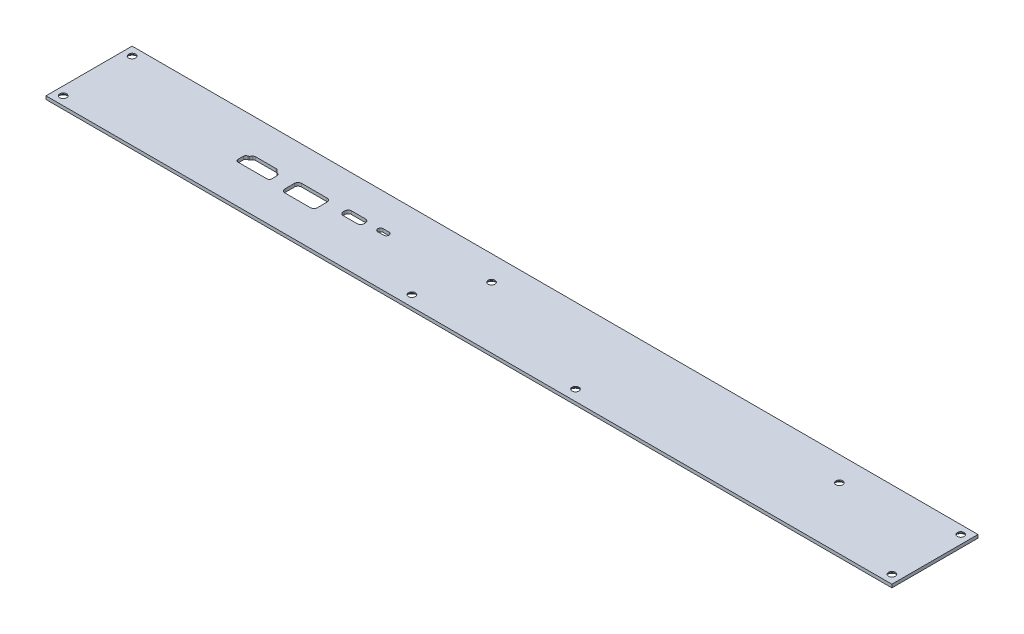
SolidWorks part; units mm, degrees
ref_plane "Ebene vorne" through (0, 0, 0) normal (0, 0, 1) x (1, 0, 0)
ref_plane "Ebene oben" through (0, 0, 0) normal (0, 1, 0) x (1, 0, 0)
ref_plane "Ebene rechts" through (0, 0, 0) normal (1, 0, 0) x (0, 0, -1)
sketch "Skizze1" plane through (0, 0, 0) normal (0, 1, 0) x (1, 0, 0)
  line L1 (-196.5, 20) -> (196.5, 20)
  line L2 (-196.5, 20) -> (-196.5, -20)
  line L3 (-196.5, -20) -> (196.5, -20)
  line L4 (196.5, 20) -> (196.5, -20)
  line L5 (-196.5, 20) -> (196.5, -20) construction
  line L6 (-196.5, -20) -> (196.5, 20) construction
  point P0 (0, 0)
extrude "Aufsatz-Linear austragen1" add sketch "Skizze1" along normal blind 1.5
sketch "Skizze2" plane through (0, 1.5, 0) normal (0, 1, 0) x (1, 0, 0)
  line L0 (196.5, -23) -> (-196.5, -23) construction
  line L5 (196.5, 20) -> (-196.5, 20) construction
  line L6 (196.5, -20) -> (196.5, 20) construction
  line L7 (196.5, 0) -> (-196.5, 0)
  line L8 (-196.5, 20) -> (-196.5, -20) construction
  line L9 (0, 20) -> (0, -20)
  line L10 (-196.5, -20) -> (196.5, -20) construction
  line L11 (143.5, 11) -> (143.4999, 6.18)
  line L12 (146, 11) -> (141, 11) construction
  line L13 (-18, 11) -> (-18, 6)
  line L14 (-20.5, 11) -> (-15.5, 11) construction
  circle A0 centre (192.5, 16) radius 1.6
  circle A1 centre (192.5, -16) radius 1.6
  circle A2 centre (-192.5, -16) radius 1.6
  circle A3 centre (-192.5, 16) radius 1.6
  circle A4 centre (44.5, -15) radius 1.6
  circle A5 centre (-31.5, -15) radius 1.6
  circle A6 centre (-18, 8.5) radius 1.6
  circle A7 centre (143.5, 8.59) radius 1.6
  dimension "D1" = 4
  dimension "D3" = 8
  dimension "D2" = 4
  dimension "D4" = 8
  dimension "D5" = 76
  dimension "D6" = 44.5
extrude "Schnitt-Linear austragen1" cut sketch "Skizze2" against normal through all contours A3 | A2 | A1 | A0 | A4 | L13 A6 | L13 A6 | L11 A7 | L11 A7 | A5
chamfer "Fase1" distance 1 angle 45 8 edges at (192.5, 0, -14.4) (192.5, 0, 17.6) (143.5, 0, -6.99) (44.5, 0, 16.6) (-18, 0, -6.9) (-31.5, 0, 16.6) (-192.5, 0, -14.4) (-192.5, 0, 17.6)
sketch "Skizze3" plane through (0, 0, 0) normal (0, -1, 0) x (1, 0, 0)
  line L0 (-89.8467, -2.7483) -> (-102.1533, 2.1843)
  line L5 (-64.7, -4.032) -> (-62, -4.032)
  line L6 (-64.7, -3.607) -> (-62, -3.607)
  line L7 (-101.9153, 2.596) -> (-90.0848, 2.596)
  line L8 (-102.5653, 1.946) -> (-102.5653, -2.51)
  line L9 (-101.9153, -3.16) -> (-90.0848, -3.16)
  line L10 (-89.4348, 1.946) -> (-89.4348, -2.51)
  line L11 (-102.5653, 2.596) -> (-89.4348, -3.16) construction
  line L12 (-102.5653, -3.16) -> (-89.4348, 2.596) construction
  line L13 (-96, -0.282) -> (-102.565, -0.282)
  line L14 (-64.7, -3.607) -> (-62, -3.607) construction
  line L15 (-64.7, -2.357) -> (-62, -2.357)
  line L16 (-64.7, -4.857) -> (-62, -4.857)
  line L17 (-96, -0.282) -> (-96, 2.596)
  line L22 (-111.8, 2.093) -> (-125.2, 2.093)
  line L23 (-126.35, 0.943) -> (-126.35, -1.5354)
  line L24 (-125.5382, -2.6346) -> (-125.0045, -2.7988)
  line L25 (-125.0045, -2.7988) -> (-124.1527, -3.7667)
  line L26 (-123.2894, -4.157) -> (-113.7106, -4.157)
  line L27 (-112.8473, -3.7667) -> (-111.9955, -2.7988)
  line L28 (-111.9955, -2.7988) -> (-111.4618, -2.6346)
  line L29 (-110.65, -1.5354) -> (-110.65, 0.943)
  line L30 (-111.8, 2.093) -> (-125.2, 2.093)
  line L31 (-126.35, 0.943) -> (-126.35, -1.5354)
  line L32 (-125.5382, -2.6346) -> (-125.0045, -2.7988)
  line L33 (-125.0045, -2.7988) -> (-124.1527, -3.7667)
  line L34 (-123.2894, -4.157) -> (-113.7106, -4.157)
  line L35 (-112.8473, -3.7667) -> (-111.9955, -2.7988)
  line L36 (-111.9955, -2.7988) -> (-111.4618, -2.6346)
  line L37 (-110.65, -1.5354) -> (-110.65, 0.943)
  line L40 (-101.9153, 3.596) -> (-90.0848, 3.596)
  line L41 (-88.4348, 1.946) -> (-88.4348, -2.51)
  line L42 (-101.9153, -4.16) -> (-90.0848, -4.16)
  line L43 (-103.5653, 1.946) -> (-103.5653, -2.51)
  line L57 (-79.225, -1.172) -> (-72.775, -1.172)
  line L58 (-71.525, -3.082) -> (-71.525, -2.422) construction
  line L59 (-71.525, -2.422) -> (-71.525, -3.082)
  line L60 (-80.475, -2.422) -> (-80.475, -3.082)
  line L62 (-79.225, -4.332) -> (-72.775, -4.332)
  line L63 (-79.225, -0.822) -> (-72.775, -0.822)
  line L64 (-71.175, -2.422) -> (-71.175, -3.082)
  line L65 (-79.225, -4.682) -> (-72.775, -4.682)
  line L66 (-80.825, -2.422) -> (-80.825, -3.082)
  line L67 (-62, -3.182) -> (-64.7, -3.182)
  line L68 (-63.35, -3.182) -> (-63.35, -4.032)
  arc A0 (-90.0848, 2.596) -> (-89.4348, 1.946) centre (-90.0848, 1.946) cw
  arc A1 (-90.0848, -3.16) -> (-89.4348, -2.51) centre (-90.0848, -2.51) ccw
  arc A2 (-101.9153, 2.596) -> (-102.5653, 1.946) centre (-101.9153, 1.946) ccw
  arc A3 (-102.5653, -2.51) -> (-101.9153, -3.16) centre (-101.9153, -2.51) ccw
  arc A4 (-79.225, -1.172) -> (-80.475, -2.422) centre (-79.225, -2.422) ccw
  arc A5 (-72.775, -1.172) -> (-71.525, -2.422) centre (-72.775, -2.422) cw
  arc A6 (-80.475, -3.082) -> (-79.225, -4.332) centre (-79.225, -3.082) ccw
  arc A7 (-71.525, -3.082) -> (-72.775, -4.332) centre (-72.775, -3.082) cw
  arc A8 (-125.2, 2.093) -> (-126.35, 0.943) centre (-125.2, 0.943) ccw
  arc A9 (-126.35, -1.5354) -> (-125.5382, -2.6346) centre (-125.2, -1.5354) ccw
  arc A10 (-124.1527, -3.7667) -> (-123.2894, -4.157) centre (-123.2894, -3.007) ccw
  arc A11 (-113.7106, -4.157) -> (-112.8473, -3.7667) centre (-113.7106, -3.007) ccw
  arc A12 (-111.4618, -2.6346) -> (-110.65, -1.5354) centre (-111.8, -1.5354) ccw
  arc A13 (-110.65, 0.943) -> (-111.8, 2.093) centre (-111.8, 0.943) ccw
  arc A14 (-125.2, 2.093) -> (-126.35, 0.943) centre (-125.2, 0.943) ccw
  arc A15 (-126.35, -1.5354) -> (-125.5382, -2.6346) centre (-125.2, -1.5354) ccw
  arc A16 (-124.1527, -3.7667) -> (-123.2894, -4.157) centre (-123.2894, -3.007) ccw
  arc A17 (-113.7106, -4.157) -> (-112.8473, -3.7667) centre (-113.7106, -3.007) ccw
  arc A18 (-111.4618, -2.6346) -> (-110.65, -1.5354) centre (-111.8, -1.5354) ccw
  arc A19 (-110.65, 0.943) -> (-111.8, 2.093) centre (-111.8, 0.943) ccw
  arc A20 (-72.775, -0.822) -> (-71.175, -2.422) centre (-72.775, -2.422) cw
  arc A21 (-71.175, -3.082) -> (-72.775, -4.682) centre (-72.775, -3.082) cw
  arc A22 (-80.825, -3.082) -> (-79.225, -4.682) centre (-79.225, -3.082) ccw
  arc A23 (-79.225, -0.822) -> (-80.825, -2.422) centre (-79.225, -2.422) ccw
  arc A28 (-64.7, -2.357) -> (-64.7, -4.857) centre (-64.7, -3.607) ccw
  arc A29 (-62, -4.857) -> (-62, -2.357) centre (-62, -3.607) ccw
  arc A30 (-90.0848, 3.596) -> (-88.4348, 1.946) centre (-90.0848, 1.946) cw
  arc A31 (-90.0848, -4.16) -> (-88.4348, -2.51) centre (-90.0848, -2.51) ccw
  arc A32 (-103.5653, -2.51) -> (-101.9153, -4.16) centre (-101.9153, -2.51) ccw
  arc A33 (-101.9153, 3.596) -> (-103.5653, 1.946) centre (-101.9153, 1.946) ccw
  spline S18 degree 3 poles (-80.475, -2.422) (-80.475, -1.6898) (-79.9572, -1.172) (-79.225, -1.172) knots 0 0 0 0 1 1 1 1 weights 1 0.804738 0.804738 1 construction
  spline S19 degree 3 poles (-72.775, -4.332) (-72.0427, -4.332) (-71.525, -3.8142) (-71.525, -3.082) knots 0 0 0 0 1 1 1 1 weights 1 0.804738 0.804738 1 construction
  point P2 (-63.35, -3.607)
  point P8 (-96, -0.282)
  point P108 (-96, -0.282)
  dimension "D3" = 1
  dimension "D1" = 0.35
  dimension "D2" = 0.35
extrude "Schnitt-Linear austragen2" cut sketch "Skizze3" against normal through all
